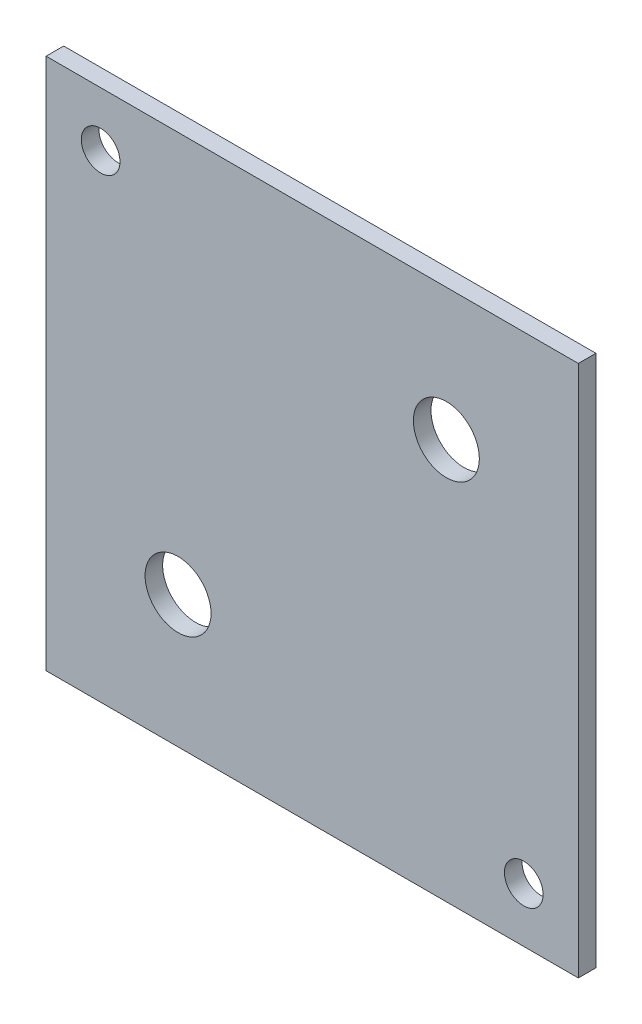
SolidWorks part; units mm, degrees
ref_plane "Plano frontal" through (0, 0, 0) normal (0, 0, 1) x (1, 0, 0)
ref_plane "Plano superior" through (0, 0, 0) normal (0, 1, 0) x (1, 0, 0)
ref_plane "Plano direito" through (0, 0, 0) normal (1, 0, 0) x (0, 0, -1)
sketch "Sketch1" plane through (0, 0, 0) normal (0, 0, 1) x (1, 0, 0)
  line L1 (-15.125, -15.125) -> (15.125, -15.125)
  line L2 (7.625, 7.625) -> (-7.625, 7.625) construction
  line L3 (7.625, 7.625) -> (7.625, -7.625) construction
  line L4 (7.625, -7.625) -> (-7.625, -7.625) construction
  line L5 (-7.625, 7.625) -> (-7.625, -7.625) construction
  line L7 (-15.125, -15.125) -> (-15.125, 15.125)
  line L11 (15.125, 15.125) -> (-15.125, 15.125)
  line L12 (15.125, 15.125) -> (15.125, -15.125)
  circle A8 centre (-7.625, -7.625) radius 1.875
  circle A9 centre (7.625, 7.625) radius 1.875
  dimension "D2" = 7.5
  dimension "D3" = 7.5
  dimension "D1" = 7.5
  dimension "D4" = 7.5
extrude "Boss-Extrude1" add sketch "Sketch1" along normal blind 1
sketch "Sketch3" plane through (0, 0, 0) normal (0, 0, -1) x (-1, 0, 0)
  line L2 (-15.125, 15.125) -> (15.125, 15.125) construction
  line L3 (15.125, 15.125) -> (15.125, -15.125) construction
  line L4 (-15.125, -15.125) -> (-15.125, 15.125) construction
  line L5 (15.125, -15.125) -> (-15.125, -15.125) construction
  circle A0 centre (12.025, 12.025) radius 1.1
  circle A1 centre (-12.025, -12.025) radius 1.1
  dimension "D1" = 3.1
  dimension "D2" = 3.1
  dimension "D3" = 3.1
  dimension "D4" = 3.1
  dimension "D5" = 2.2
extrude "Cut-Extrude1" cut sketch "Sketch3" against normal up to surface (1 mm away) up to face at (-5.75, -7.625, 1)
equation "\"D1@Sketch1\"=\"D4@Sketch1\""
equation "\"D2@Sketch1\"=\"D1@Sketch1\""
equation "\"D3@Sketch1\"=\"D2@Sketch1\""
equation "\"D2@Sketch3\"=\"D1@Sketch3\""
equation "\"D3@Sketch3\"=\"D2@Sketch3\""
equation "\"D4@Sketch3\"=\"D3@Sketch3\""
equation "\"D1@Sketch3\"=(\"D5@Sketch3\"/2)+2"
